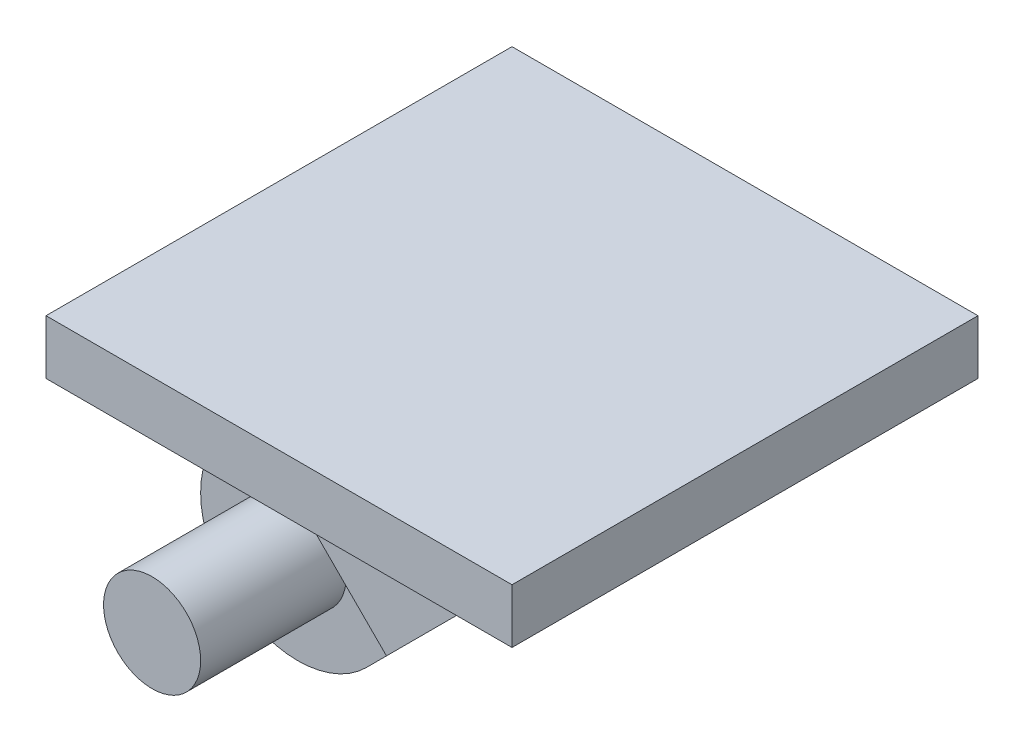
SolidWorks part; units mm, degrees
ref_plane "前视基准面" through (0, 0, 0) normal (0, 0, 1) x (1, 0, 0)
ref_plane "上视基准面" through (0, 0, 0) normal (0, 1, 0) x (1, 0, 0)
ref_plane "右视基准面" through (0, 0, 0) normal (1, 0, 0) x (0, 0, -1)
other "Configuration Table"
sketch "草图1" plane through (0, 0, 0) normal (0, 1, 0) x (1, 0, 0)
  line L1 (-30, -30) -> (30, -30)
  line L2 (-30, -30) -> (-30, 30)
  line L3 (-30, 30) -> (30, 30)
  line L4 (30, -30) -> (30, 30)
  line L5 (-30, -30) -> (30, 30) construction
  line L6 (-30, 30) -> (30, -30) construction
  point P0 (0, 0)
  dimension "D1" = 60
  dimension "D2" = 60
extrude "凸台-拉伸1" add sketch "草图1" along normal blind 7
sketch "草图2" plane through (0, 0, 0) normal (0, 0, 1) x (1, 0, 0)
  line L0 (-12.5, 0) -> (12.5, 0)
  line L1 (-30, 0) -> (30, 0) construction
  line L2 (-12.5, 0) -> (5.1777, -17.6777) construction
  line L3 (-12.5, 0) -> (-30.1777, -17.6777)
  line L4 (-30.1777, -17.6777) -> (-12.5, -35.3553) construction
  line L5 (-12.5, -35.3553) -> (5.1777, -17.6777)
  arc A0 (5.1777, -17.6777) -> (12.5, 0) centre (-12.5, 0) ccw
  arc A1 (-30.1777, -17.6777) -> (-12.5, -35.3553) centre (-21.3388, -26.5165) ccw
  point P6 (0, 0)
  dimension "D1" = 25
  dimension "D2" = 45
  dimension "D3" = 25
extrude "凸台-拉伸2" add sketch "草图2" along normal blind 12.5 and the other way blind 12.5
sketch "草图3" plane through (0, 0, 0) normal (0, 0, 1) x (1, 0, 0)
  line L0 (-21.3388, -8.8388) -> (-3.6612, -26.5165)
  line L1 (-12.5, 0) -> (-30.1777, -17.6777) construction
  line L2 (-12.5, -35.3553) -> (5.1777, -17.6777) construction
  line L3 (12.5, 0) -> (-12.5, 0) construction
  line L6 (-21.3388, -8.8388) -> (-30.1777, -17.6777)
  line L7 (-3.6612, -26.5165) -> (-12.5, -35.3553)
  arc A0 (-30.1777, -17.6777) -> (-12.5, -35.3553) centre (-21.3388, -26.5165) ccw
  dimension "D2" = 45
extrude "切除-拉伸1" cut sketch "草图3" along normal blind 6.25 from surface at -12.5 starting at face at (-8.9161, -16.0556, -12.5)
sketch "草图4" plane through (0, 0, 0) normal (0, 0, 1) x (1, 0, 0)
  line L3 (-3.6612, -26.5165) -> (-21.3388, -8.8388)
  line L4 (-12.5, -35.3553) -> (-3.6612, -26.5165)
  line L5 (-21.3388, -8.8388) -> (-30.1777, -17.6777)
  line L6 (-3.6612, -26.5165) -> (-21.3388, -8.8388)
  line L7 (-12.5, -35.3553) -> (-3.6612, -26.5165)
  line L8 (-21.3388, -8.8388) -> (-30.1777, -17.6777)
  arc A1 (-30.1777, -17.6777) -> (-12.5, -35.3553) centre (-21.3388, -26.5165) ccw
  arc A2 (-30.1777, -17.6777) -> (-12.5, -35.3553) centre (-21.3388, -26.5165) ccw
  dimension "D1" = 0
extrude "切除-拉伸2" cut sketch "草图4" against normal blind 6.25 from surface at 12.5 starting at face at (-8.9161, -16.0556, 12.5)
sketch "草图5" plane through (0, 0, 0) normal (0, 0, 1) x (1, 0, 0)
  circle A0 centre (-21.3388, -26.5165) radius 6.25
  dimension "D1" = 12.5
extrude "凸台-拉伸3" add sketch "草图5" along normal blind 25 and the other way blind 25
ref_plane "基准面1" through (2.5888, -2.5888, 0) normal (0.7071, -0.7071, 0) x (-0.7071, -0.7071, 0)
sketch "草图6" plane through (2.5888, -2.5888, 0) normal (0.7071, -0.7071, 0) x (-0.7071, -0.7071, 0)
  line L0 (33.8388, -75) -> (33.8388, 75)
  line L2 (40.0888, 25) -> (27.5888, 25) construction
  line L3 (40.0888, 25) -> (27.5888, 25) construction
  point P3 (33.8388, 0)
  point P4 (33.8388, 25)
  dimension "D1" = 150
